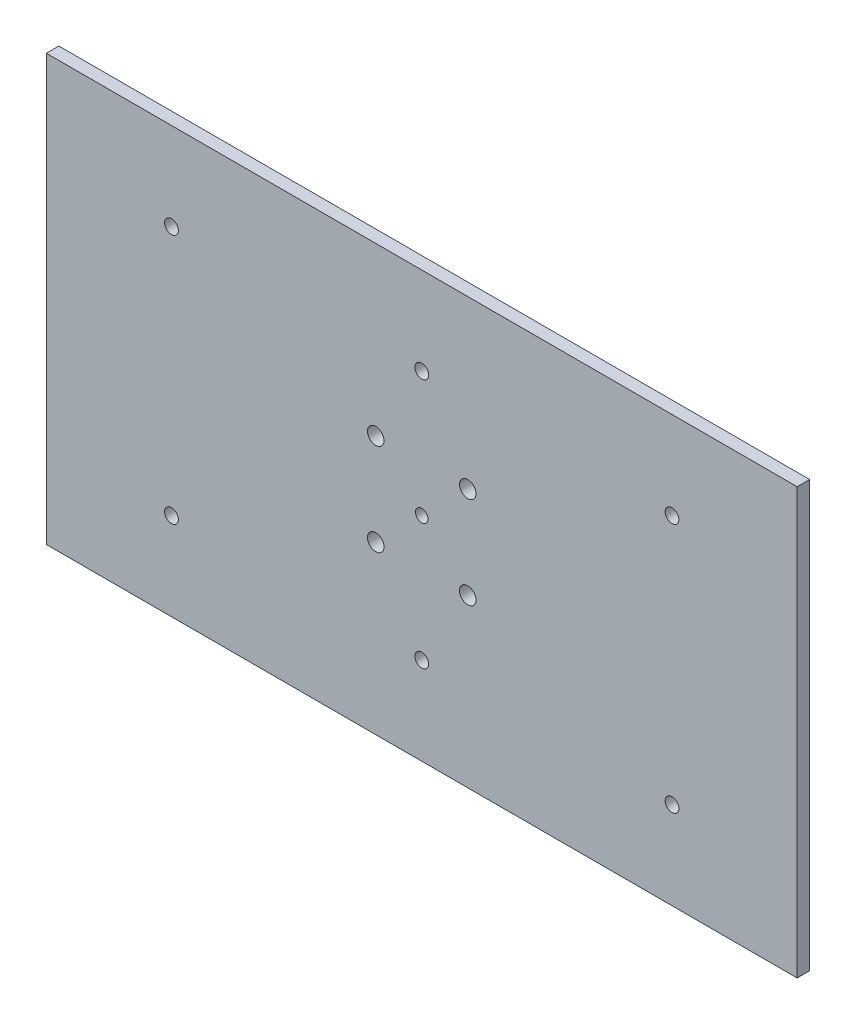
SolidWorks part; units mm, degrees
ref_plane "前视基准面" through (0, 0, 0) normal (0, 0, 1) x (1, 0, 0)
ref_plane "上视基准面" through (0, 0, 0) normal (0, 1, 0) x (1, 0, 0)
ref_plane "右视基准面" through (0, 0, 0) normal (1, 0, 0) x (0, 0, -1)
sketch "草图1" plane through (0, 0, 0) normal (0, 0, 1) x (1, 0, 0)
  line L0 (-18.3848, 18.3848) -> (0, 0) construction
  line L1 (150, -125) -> (-150, -125)
  line L2 (150, -125) -> (150, 125)
  line L3 (150, 125) -> (-150, 125)
  line L4 (-150, -125) -> (-150, 125)
  line L5 (150, -125) -> (-150, 125) construction
  line L6 (150, 125) -> (-150, -125) construction
  line L7 (0, 0) -> (0, 75.2853) construction
  line L8 (0, 0) -> (89.5261, 0) construction
  circle A0 centre (-18.3848, 18.3848) radius 3.3
  circle A1 centre (18.3848, 18.3848) radius 3.3
  circle A2 centre (18.3848, -18.3848) radius 3.3
  circle A3 centre (-18.3848, -18.3848) radius 3.3
  circle A4 centre (0, 0) radius 2.5
  point P0 (0, 0)
  dimension "D3" = 6.6
  dimension "D6" = 5
  dimension "D1" = 250
  dimension "D2" = 300
  dimension "D4" = 26
  dimension "D5" = 45
extrude "凸台-拉伸1" add sketch "草图1" along normal blind 5
sketch "草图2" plane through (0, 0, 5) normal (0, 0, 1) x (1, 0, 0)
  line L0 (-150, 0) -> (150, 0) construction
  line L1 (-150, 125) -> (-150, -125) construction
  line L2 (150, -125) -> (150, 125) construction
  line L3 (0, 125) -> (0, -125) construction
  line L4 (150, 125) -> (-150, 125) construction
  line L5 (-150, -125) -> (150, -125) construction
  line L7 (100, -50) -> (-100, -50) construction
  line L8 (100, -50) -> (100, 50) construction
  line L9 (100, 50) -> (-100, 50) construction
  line L10 (-100, -50) -> (-100, 50) construction
  line L11 (100, -50) -> (-100, 50) construction
  line L12 (100, 50) -> (-100, -50) construction
  circle A0 centre (-100, 50) radius 2.75
  circle A1 centre (0, 50) radius 2.75
  circle A2 centre (100, 50) radius 2.75
  circle A3 centre (100, -50) radius 2.75
  circle A4 centre (0, -50) radius 2.75
  circle A5 centre (-100, -50) radius 2.75
  point P12 (0, 0)
  dimension "D1" = 5.5
  dimension "D2" = 100
  dimension "D3" = 200
extrude "切除-拉伸1" cut sketch "草图2" against normal through all
sketch "草图3" plane through (0, 0, 5) normal (0, 0, 1) x (1, 0, 0)
  line L0 (150, -125) -> (150, 125) construction
  line L1 (-150, 125) -> (150, 125)
  line L2 (-150, 125) -> (-150, 85)
  line L3 (-150, 85) -> (150, 85)
  line L4 (150, 125) -> (150, 85)
  line L6 (-150, -125) -> (150, -125)
  line L7 (-150, -125) -> (-150, -85)
  line L8 (-150, -85) -> (150, -85)
  line L9 (150, -125) -> (150, -85)
  dimension "D1" = 40
extrude "切除-拉伸2" cut sketch "草图3" against normal through all
